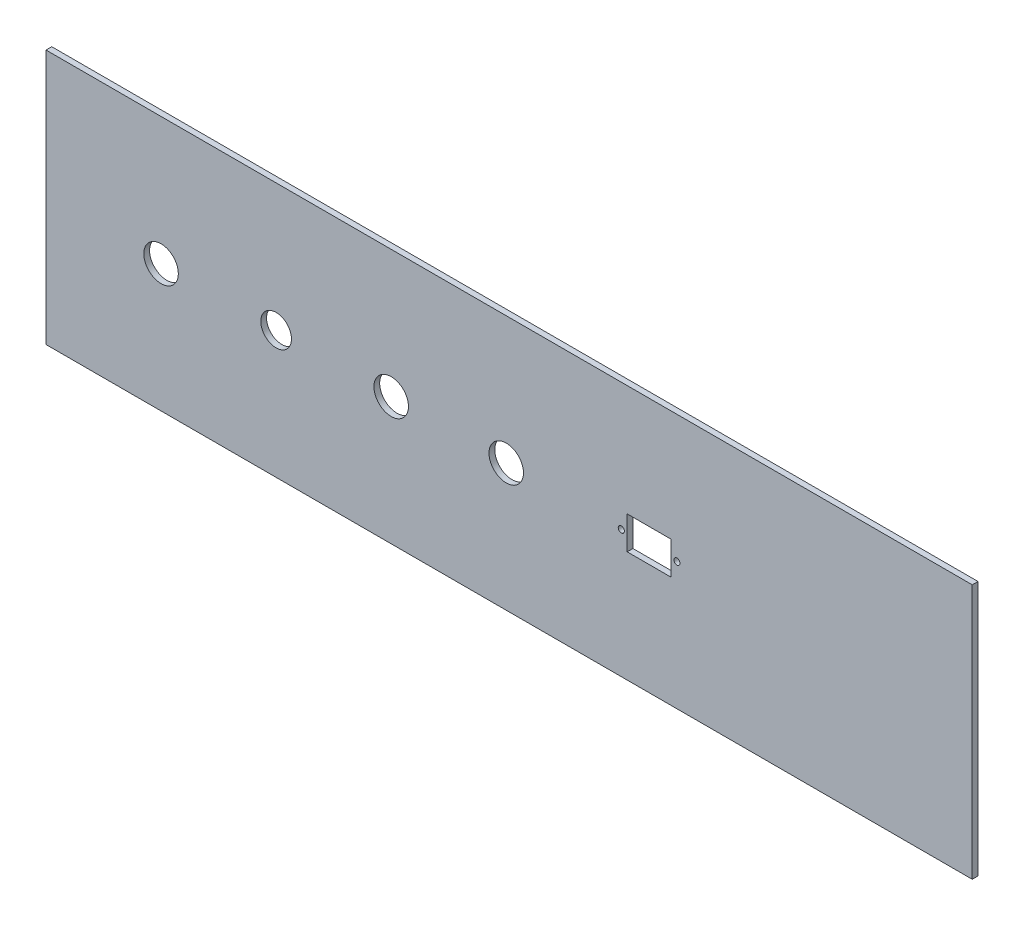
SolidWorks part; units mm, degrees
ref_plane "Plan de face" through (0, 0, 0) normal (0, 0, 1) x (1, 0, 0)
ref_plane "Plan de dessus" through (0, 0, 0) normal (0, 1, 0) x (1, 0, 0)
ref_plane "Plan de droite" through (0, 0, 0) normal (1, 0, 0) x (0, 0, -1)
sketch "Esquisse1" plane through (0, 0, 0) normal (0, 0, 1) x (1, 0, 0)
  line L1 (-411.72, 119.63) -> (71.28, 119.63)
  line L2 (-411.72, 119.63) -> (-411.72, -13.37)
  line L3 (-411.72, -13.37) -> (71.28, -13.37)
  line L4 (71.28, 119.63) -> (71.28, -13.37)
  line L5 (-108.65, 61.695) -> (-85.79, 61.695)
  line L6 (-108.65, 61.695) -> (-108.65, 44.545)
  line L7 (-108.65, 44.545) -> (-85.79, 44.545)
  line L8 (-85.79, 61.695) -> (-85.79, 44.545)
  circle A0 centre (-291.72, 53.13) radius 8
  circle A1 centre (-351.72, 53.13) radius 9
  circle A2 centre (-231.72, 53.13) radius 9
  circle A3 centre (-171.72, 53.13) radius 9
  circle A4 centre (-111.72, 53.12) radius 1.6
  circle A5 centre (-82.72, 53.12) radius 1.6
  dimension "D3" = 16
  dimension "D4" = 18
  dimension "D5" = 18
  dimension "D6" = 18
  dimension "D7" = 60
  dimension "D8" = 66.5
  dimension "D9" = 60
  dimension "D10" = 66.5
  dimension "D11" = 60
  dimension "D12" = 66.5
  dimension "D13" = 60
  dimension "D14" = 66.5
  dimension "D18" = 29
  dimension "D19" = 3.07
  dimension "D20" = 3.2
  dimension "D21" = 3.2
  dimension "D22" = 60
  dimension "D23" = 8.575
  dimension "D1" = 133
  dimension "D2" = 483
  dimension "D15" = 22.86
  dimension "D16" = 17.15
  dimension "D17" = 57.915
extrude "Boss.-Extru.1" add sketch "Esquisse1" along normal blind 3
